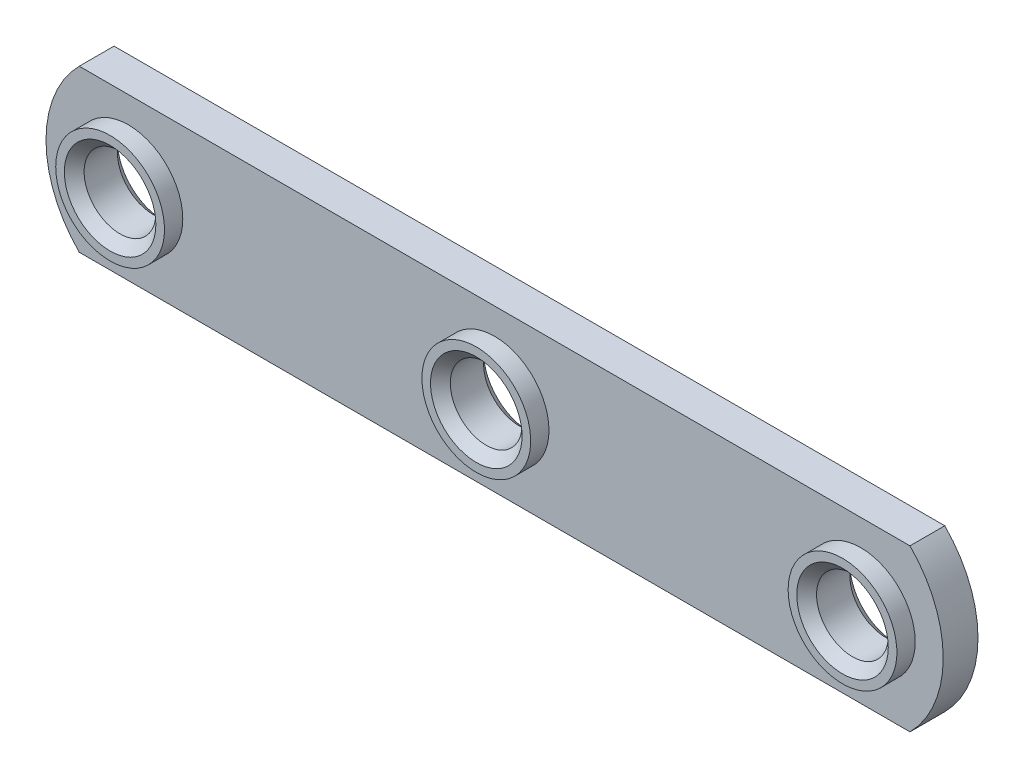
SolidWorks part; units mm, degrees
ref_plane "Front Plane" through (0, 0, 0) normal (0, 0, 1) x (1, 0, 0)
ref_plane "Top Plane" through (0, 0, 0) normal (0, 1, 0) x (1, 0, 0)
ref_plane "Right Plane" through (0, 0, 0) normal (1, 0, 0) x (0, 0, -1)
ref_plane "Plane1" through (0, 0, 1.2065) normal (0, 0, 1) x (1, 0, 0)
sketch "Sketch1" plane through (0, 0, 1.2065) normal (0, 0, 1) x (1, 0, 0)
  line L0 (54.2095, 5.588) -> (-3.4095, 5.588)
  line L1 (-3.4095, -5.588) -> (54.2095, -5.588)
  arc A0 (-3.4095, 5.588) -> (-3.4095, -5.588) centre (2.2098, 0) ccw
  arc A1 (54.2095, -5.588) -> (54.2095, 5.588) centre (48.5902, 0) ccw
extrude "Boss-Extrude1" add sketch "Sketch1" against normal blind 2.413
ref_plane "Plane2" through (0, 0, 0) normal (0, -1, 0) x (1, 0, 0)
sketch "Sketch2" plane through (0, 0, 0) normal (0, -1, 0) x (1, 0, 0)
  line L0 (29.1719, 2.4765) -> (25.4, 2.4765)
  line L1 (25.4, 2.4765) -> (25.4, 1.2065)
  line L2 (25.4, 1.2065) -> (29.1719, 1.2065)
  line L3 (29.1719, 1.2065) -> (29.1719, 2.4765)
  line L4 (25.4, 2.4765) -> (25.4, 1.2065) construction
revolve "Revolve1" add sketch "Sketch2" angle 360 about L4
sketch "Sketch3" plane through (0, 0, 0) normal (0, -1, 0) x (1, 0, 0)
  line L0 (3.7719, 2.4765) -> (0, 2.4765)
  line L1 (0, 2.4765) -> (0, 1.2065)
  line L2 (0, 1.2065) -> (3.7719, 1.2065)
  line L3 (3.7719, 1.2065) -> (3.7719, 2.4765)
  line L4 (0, 2.4765) -> (0, 1.2065) construction
revolve "Revolve2" add sketch "Sketch3" angle 360 about L4
sketch "Sketch4" plane through (0, 0, 0) normal (0, -1, 0) x (1, 0, 0)
  line L0 (54.5719, 2.4765) -> (50.8, 2.4765)
  line L1 (50.8, 2.4765) -> (50.8, 1.2065)
  line L2 (50.8, 1.2065) -> (54.5719, 1.2065)
  line L3 (54.5719, 1.2065) -> (54.5719, 2.4765)
  line L4 (50.8, 2.4765) -> (50.8, 1.2065) construction
revolve "Revolve3" add sketch "Sketch4" angle 360 about L4
hole_wizard "Hole1" positions "Sketch6" profile "Sketch5" legacy
sketch "Sketch6" plane through (0, 0, 2.4765) normal (0, 0, 1) x (1, 0, 0)
  point P0 (0, 0)
  point P1 (25.4, 0)
  point P2 (50.8, 0)
sketch "Sketch5" plane through (0, 0, 2.4765) normal (1, 0, 0) x (0, -1, 0)
  line L0 (0, 0) -> (0, 3.683)
  line L1 (0, 3.683) -> (2.4879, 3.683)
  line L2 (2.4879, 3.683) -> (2.4879, 0.6871)
  line L3 (2.4879, 0.6871) -> (3.175, 0)
  line L4 (3.175, 0) -> (0, 0)
  line L5 (0, -6.4453) -> (0, 115.525) construction
  line L6 (-2.4879, 0.6871) -> (-3.175, 0) construction
  dimension "Diameter" = 4.9759
  dimension "Depth" = 3.683
  dimension "C-Sink Angle" = 90
  dimension "C-Sink Diameter" = 6.35
chamfer "Chamfer1" distance 0.6871 angle 45 3 edges at (2.4879, 0, -1.2065) (53.2879, 0, -1.2065) (27.8879, 0, -1.2065)
